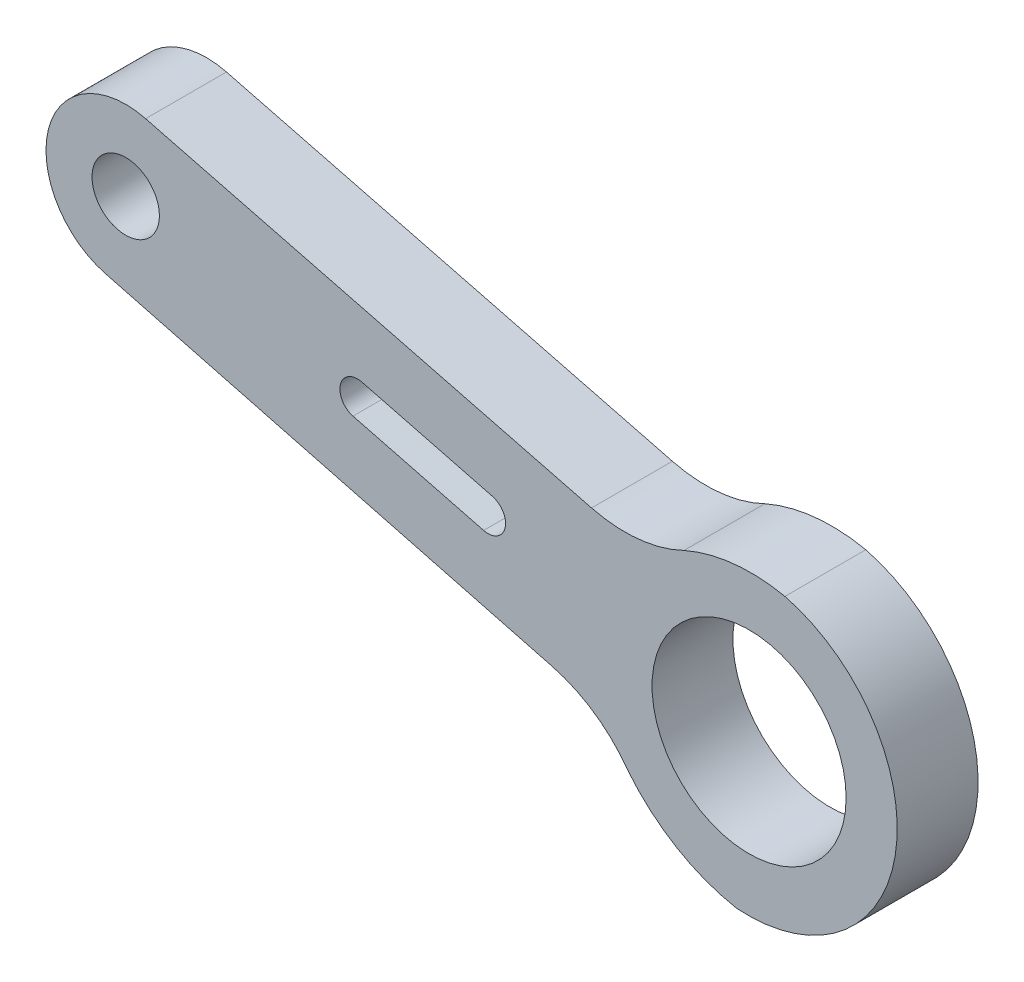
SolidWorks part; units mm, degrees
ref_plane "前基準面" through (0, 0, 0) normal (0, 0, 1) x (1, 0, 0)
ref_plane "上基準面" through (0, 0, 0) normal (0, 1, 0) x (1, 0, 0)
ref_plane "右基準面" through (0, 0, 0) normal (1, 0, 0) x (0, 0, -1)
sketch "草圖1" plane through (0, 0, 0) normal (0, 0, 1) x (1, 0, 0)
  line L0 (257.9811, 79.0107) -> (253.1345, 80.2602) construction
  line L1 (252.804, 79.0029) -> (257.6506, 77.7534) construction
  line L2 (243.6355, 78.984) -> (260.1675, 74.6641) construction
  line L3 (261.6542, 80.477) -> (245.112, 84.7111) construction
  line L4 (257.9811, 79.0107) -> (253.1345, 80.2602)
  line L5 (252.804, 79.0029) -> (257.6506, 77.7534)
  line L6 (243.6355, 78.984) -> (260.1675, 74.6641)
  line L7 (261.6542, 80.477) -> (245.112, 84.7111)
  circle A0 centre (267.4995, 75.8854) radius 3.6 construction
  arc A1 (268.8301, 81.2221) -> (265.0866, 80.8279) centre (267.5683, 75.2322) ccw construction
  arc A2 (261.6542, 80.477) -> (265.0866, 80.8279) centre (262.8931, 85.321) ccw construction
  arc A3 (263.01, 72.7083) -> (260.1675, 74.6641) centre (258.9286, 69.8201) ccw construction
  circle A4 centre (244.3738, 81.8476) radius 1.25 construction
  arc A5 (253.1345, 80.2602) -> (252.804, 79.0029) centre (252.9693, 79.6315) ccw construction
  arc A6 (257.6506, 77.7534) -> (257.9811, 79.0107) centre (257.8158, 78.382) ccw construction
  circle A7 centre (267.4995, 75.8854) radius 3.6
  arc A8 (268.8301, 81.2221) -> (265.0866, 80.8279) centre (267.5683, 75.2322) ccw
  arc A9 (261.6542, 80.477) -> (265.0866, 80.8279) centre (262.8931, 85.321) ccw
  arc A10 (263.01, 72.7083) -> (260.1675, 74.6641) centre (258.9286, 69.8201) ccw
  circle A11 centre (244.3738, 81.8476) radius 1.25
  arc A12 (253.1345, 80.2602) -> (252.804, 79.0029) centre (252.9693, 79.6315) ccw
  arc A13 (257.6506, 77.7534) -> (257.9811, 79.0107) centre (257.8158, 78.382) ccw
  arc A14 (243.6355, 78.984) -> (245.112, 84.7111) centre (244.3738, 81.8476) cw
  arc A15 (268.8301, 81.2221) -> (272.9726, 76.3442) centre (267.4414, 75.8448) cw
  arc A16 (272.9726, 76.3442) -> (268.8301, 81.2221) centre (267.4414, 75.8448) ccw construction
  arc A17 (272.9726, 76.3442) -> (268.3079, 70.3592) centre (267.4414, 75.8448) cw
  arc A18 (263.01, 72.7083) -> (267.0277, 70.3066) centre (268.2735, 76.952) ccw
  arc A19 (263.01, 72.7083) -> (267.0277, 70.3066) centre (268.2735, 76.952) ccw construction
  arc A20 (267.0277, 70.3066) -> (268.3079, 70.3592) centre (267.4414, 75.8448) ccw
  point P0 (257.6506, 77.7534)
extrude "填料-伸長1" add sketch "草圖1" along normal blind 3
